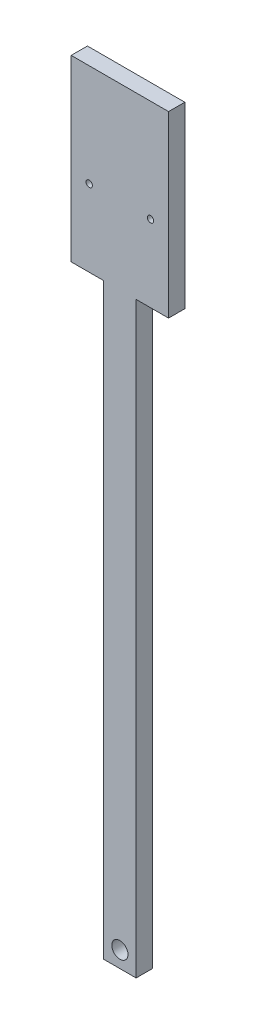
SolidWorks part; units mm, degrees
ref_plane "Alzado" through (0, 0, 0) normal (0, 0, 1) x (1, 0, 0)
ref_plane "Planta" through (0, 0, 0) normal (0, 1, 0) x (1, 0, 0)
ref_plane "Vista lateral" through (0, 0, 0) normal (1, 0, 0) x (0, 0, -1)
sketch "Croquis1" plane through (0, 0, 0) normal (0, 1, 0) x (1, 0, 0)
  line L1 (-6.35, 3.175) -> (6.35, 3.175)
  line L2 (-6.35, 3.175) -> (-6.35, -3.175)
  line L3 (-6.35, -3.175) -> (6.35, -3.175)
  line L4 (6.35, 3.175) -> (6.35, -3.175)
  line L5 (-6.35, 3.175) -> (6.35, -3.175) construction
  line L6 (-6.35, -3.175) -> (6.35, 3.175) construction
  point P0 (0, 0)
  dimension "D1" = 6.35
  dimension "D2" = 12.7
extrude "Saliente-Extruir1" add sketch "Croquis1" along normal mid plane 300
sketch "Croquis2" plane through (0, 0, 0) normal (0, 0, 1) x (1, 0, 0)
  line L0 (-6.35, -150) -> (6.35, -150) construction
  circle A0 centre (0, -143.65) radius 3.175
  dimension "D1" = 6.35
  dimension "D2" = 6.35
extrude "Cortar-Extruir1" cut sketch "Croquis2" against normal through all both and the other way through all
sketch "Croquis3" plane through (0, 150, 0) normal (0, 1, 0) x (1, 0, 0)
  line L0 (-6.35, -3.175) -> (6.35, -3.175) construction
  line L1 (-19.05, 3.175) -> (19.05, 3.175)
  line L2 (-19.05, 3.175) -> (-19.05, -3.175)
  line L3 (-19.05, -3.175) -> (19.05, -3.175)
  line L4 (19.05, 3.175) -> (19.05, -3.175)
  line L5 (-19.05, 3.175) -> (19.05, -3.175) construction
  line L6 (-19.05, -3.175) -> (19.05, 3.175) construction
  point P0 (0, 0)
  dimension "D1" = 38.1
extrude "Saliente-Extruir2" add sketch "Croquis3" against normal blind 70
hole_wizard "Taladro roscado M31" positions "Croquis4" profile "Croquis5" tap size "M3" standard "DIN" end condition through all
sketch "Croquis4" plane through (0, 0, -3.175) normal (0, 0, -1) x (-1, 0, 0)
  point P0 (12, 110)
  point P3 (-12, 110)
sketch "Croquis5" plane through (-12, 110, -3.175) normal (1, 0, 0) x (0, 1, 0)
  line L0 (0, 0) -> (0, 6.35)
  line L1 (0, 6.35) -> (1.25, 6.35)
  line L2 (1.25, 6.35) -> (1.25, 0.275)
  line L3 (1.25, 0.275) -> (1.525, 0)
  line L5 (1.525, 0) -> (0, 0)
  line L6 (-1.25, 0.275) -> (-1.525, 0) construction
  line L11 (0, -6.35) -> (0, 107.95) construction
  dimension "Diámetro de perforador para roscar hasta el siguiente" = 2.5
  dimension "Profundidad de perforador para roscar hasta el siguiente" = 6.35
  dimension "Diámetro de avellanado cercano" = 3.05
  dimension "Ángulo de avellanado cercano" = 90
cosmetic thread "Rosca de taladro1" parameters "D2"=3
cosmetic thread "Rosca de taladro2" parameters "D2"=3
equation "\"D2@Croquis2\"=\"D1@Croquis2\""
